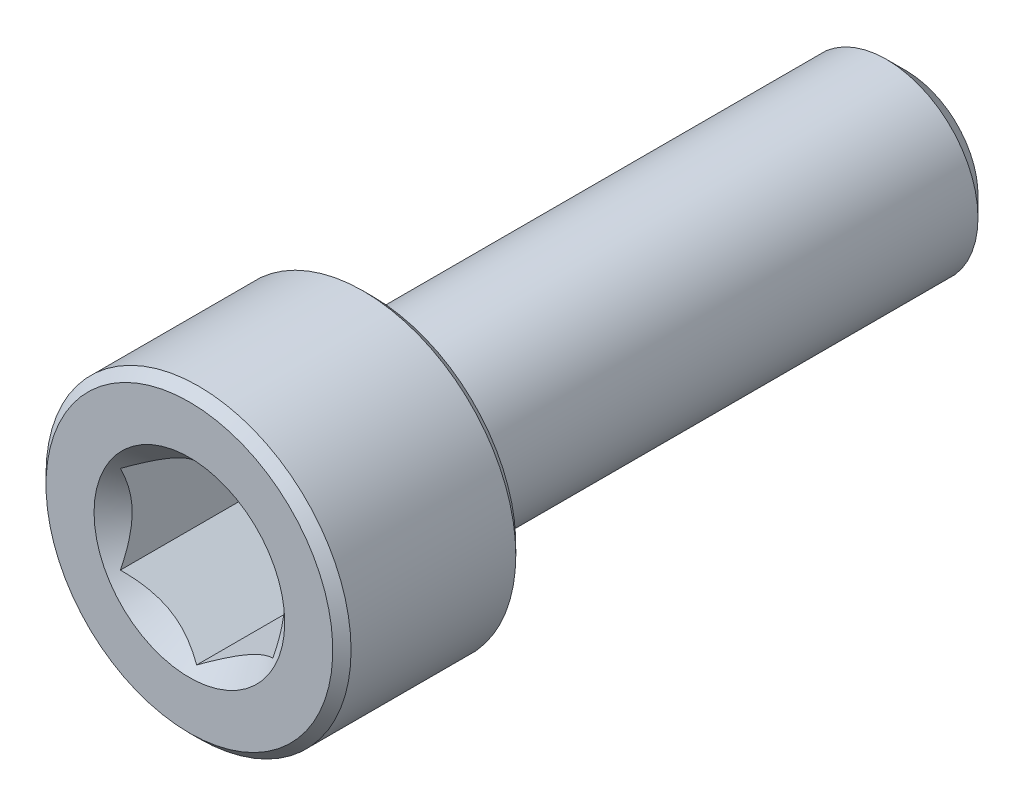
SolidWorks part; units mm, degrees
ref_plane "Front Plane" through (0, 0, 0) normal (0, 0, 1) x (1, 0, 0)
ref_plane "Top Plane" through (0, 0, 0) normal (0, 1, 0) x (1, 0, 0)
ref_plane "Right Plane" through (0, 0, 0) normal (1, 0, 0) x (0, 0, -1)
sketch "Sketch1" plane through (0, 0, 0) normal (1, 0, 0) x (0, 0, -1)
  line L0 (-10.5, 0) -> (10.5, 0) construction
  line L1 (10.5, 0) -> (10.5, 2.3505) construction
  line L2 (10.5, 2.3505) -> (9.8505, 3) construction
  line L3 (9.8505, 3) -> (9.75, 3) construction
  line L4 (9.75, 3) -> (-4.5, 3) construction
  line L5 (-4.5, 3) -> (-4.5, 5) construction
  line L6 (-4.5, 5) -> (-10.5, 5) construction
  line L7 (-10.5, 5) -> (-10.5, 0) construction
  line L8 (10.5, 2.3505) -> (10.5, 3) construction
  line L9 (10.4375, 3.1083) -> (10.9375, 2.2422) construction
  line L10 (10.9375, 2.2422) -> (11.4375, 3.1083) construction
  line L11 (11.4375, 3.1083) -> (10.4375, 3.1083) construction
  line L12 (10.9375, 3.1083) -> (10.9375, 3) construction
  line L13 (10.9375, 2.2422) -> (10.9375, 2.3505) construction
  line L14 (10.875, 2.3505) -> (11, 2.3505) construction
  line L15 (10.5, 3) -> (11.375, 3) construction
  line L16 (10.4687, 3.0541) -> (11.4062, 3.0541) construction
  line L17 (10.5, 0) -> (10.5, -3) construction
  line L18 (-4.8, 5) -> (-4.5, 4.7) construction
  line L19 (-10.2, 5) -> (-10.5, 4.7) construction
  line L20 (-4.5, 3) -> (-4.5, 0) construction
  line L21 (-4.5, 1.5) -> (0.5, 1.5) construction
  line L22 (0.5, 1.5) -> (5.5, 1.5) construction
  line L23 (5.5, 1.5) -> (10.5, 1.5) construction
  line L24 (0.5, 1.5) -> (0.5, 3) construction
  line L25 (0.5, 3) -> (0.5, 5) construction
  line L26 (5.5, 1.5) -> (5.5, 5) construction
  point P0 (-10.5, 2.5)
  point P3 (8, 3)
  point P4 (0, 0)
  point P18 (5.5, 3)
  point P22 (10.9375, 2.3505)
  point P24 (9.75, 3)
  point P25 (10.9375, 3)
  point P28 (10.9375, 3.0541)
  point P29 (8, -3)
  point P30 (0.5, 3)
  point P31 (-7.5, 5)
  point P37 (-5.55, 5)
  point P38 (-10.05, 5)
  point P45 (0.5, 1.5)
  point P46 (5.5, 1.5)
  dimension "D2" = 0.125
  dimension "D7" = 0.3
  dimension "D8" = 0.3
  dimension "D9" = 0.3
  dimension "D10" = 0.15
  dimension "D11" = 0.75
  dimension "Drive Size" = 5
  dimension "Head Diameter" = 10
  dimension "Head Height" = 6
  dimension "Thread Pitch" = 1
  dimension "Thread Size" = 6
  dimension "Length" = 15
  dimension "D12" = 0.75
  dimension "D4" = 2.5
  dimension "D3" = 45
sketch "Sketch2" plane through (0, 0, 0) normal (1, 0, 0) x (0, 0, -1)
  line L0 (-10.5, 0) -> (-10.5, 4.7)
  line L1 (-10.2, 5) -> (-4.8, 5)
  line L2 (-4.5, 4.7) -> (-4.5, 3.3)
  line L4 (9.8505, 3) -> (10.5, 2.3505)
  line L5 (10.5, 2.3505) -> (10.5, 0)
  line L6 (-4.5, 5) -> (-10.5, 5) construction
  line L7 (10.5, 0) -> (-10.5, 0)
  line L8 (-10.2, 5) -> (-10.5, 4.7) construction
  line L10 (-10.2, 5) -> (-10.5, 4.7)
  line L14 (-4.8, 5) -> (-4.5, 4.7) construction
  line L16 (-4.8, 5) -> (-4.5, 4.7)
  line L17 (-4.5, 3) -> (-4.5, 5) construction
  line L19 (-4.2, 3) -> (9.8505, 3)
  line L20 (9.75, 3) -> (-4.5, 3) construction
  arc A1 (-4.5, 3.3) -> (-4.2, 3) centre (-4.2, 3.3) ccw
  dimension "D3" = 0.3
revolve "Revolve1" add sketch "Sketch2" angle 360 about L7
sketch "Sketch3" plane through (0, 0, 10.5) normal (0, 0, 1) x (1, 0, 0)
  line L1 (2.5, -1.4434) -> (2.5, 1.4434)
  line L2 (2.5, 1.4434) -> (0, 2.8868)
  line L3 (0, 2.8868) -> (-2.5, 1.4434)
  line L4 (-2.5, 1.4434) -> (-2.5, -1.4434)
  line L5 (-2.5, -1.4434) -> (0, -2.8868)
  line L6 (0, -2.8868) -> (2.5, -1.4434)
  circle A0 centre (0, 0) radius 2.5 construction
  circle A1 centre (0, 0) radius 5 construction
  circle A2 centre (0, 0) radius 5 construction
  circle A3 centre (0, 0) radius 2.8868 construction
  point P13 (0, 0)
extrude "Cut-Extrude1" cut sketch "Sketch3" against normal offset from surface (5 mm away) 1 up to face at (0, 4.7, 4.5)
sketch "Sketch4" plane through (0, 0, 10.5) normal (0, 0, 1) x (1, 0, 0)
  circle A0 centre (0, 0) radius 3.125
  dimension "D1" = 6.25
extrude "Cut-Extrude2" cut sketch "Sketch4" against normal up to vertex (3 mm away) draft 45 up to point (0, 5, 7.5)
sketch "Sketch11" plane through (0, 0, 0) normal (1, 0, 0) x (0, 0, -1)
  line L0 (-10.5, 0) -> (10.5, 0) construction
  line L1 (-10.5, 0) -> (10.5, 0) construction
  line L2 (-1.6875, 0) -> (-1.6875, 3) construction
  line L3 (9.75, 3) -> (-4.5, 3) construction
  line L4 (7.6875, 0) -> (7.6875, 3) construction
  line L6 (10.5, 2.3505) -> (10.5, 3) construction
  point P2 (-1.6875, 0)
  point P3 (7.6875, 0)
  dimension "D1" = 2.8125
  dimension "D2" = 2.8125
split "Split1" trim tools "Front Plane" bodies to split 106 resulting bodies 120 121
move or copy body "Body-Move/Copy1" bodies to move or copy 121 copy no translate (0, 0, -2.5) parameters "D1"=0, "D2"=0, "D3"=2.5
sketch "Sketch12" plane through (0, 0, -2.5) normal (0, 0, 1) x (1, 0, 0)
  circle A1 centre (0, 0) radius 3
  circle A2 centre (0, 0) radius 3
  dimension "D1" = 0
extrude "Boss-Extrude1" add sketch "Sketch12" along normal up to surface (2.5 mm away) up to face at (3, 0, 0)
equation "\"D2@Sketch1\" = \"Thread Pitch@Sketch1\" / 8"
equation "\"D7@Sketch1\" = \"Head Height@Sketch1\" * .05"
equation "\"D8@Sketch1\"=\"D7@Sketch1\""
equation "\"D9@Sketch1\"=\"D7@Sketch1\""
equation "\"D10@Sketch1\"=\"D7@Sketch1\"/2"
equation "\"D11@Sketch1\"=\"D10@Sketch1\"*5"
equation "\"D4@Sketch1\"=\"Thread Pitch@Sketch1\"*2.5"
equation "\"D12@Sketch1\"=\"Thread Pitch@Sketch1\"*.75"
equation "\"D3@Sketch2\" = \"Thread Size@Sketch1\" * 0.05"
equation "\"D1@Sketch11\"=\"Length@Sketch1\"*0.1875"
equation "\"D2@Sketch11\"=\"D1@Sketch11\""
equation "\"D1@Sketch4\"=\"Drive Size@Sketch1\"*1.25"
